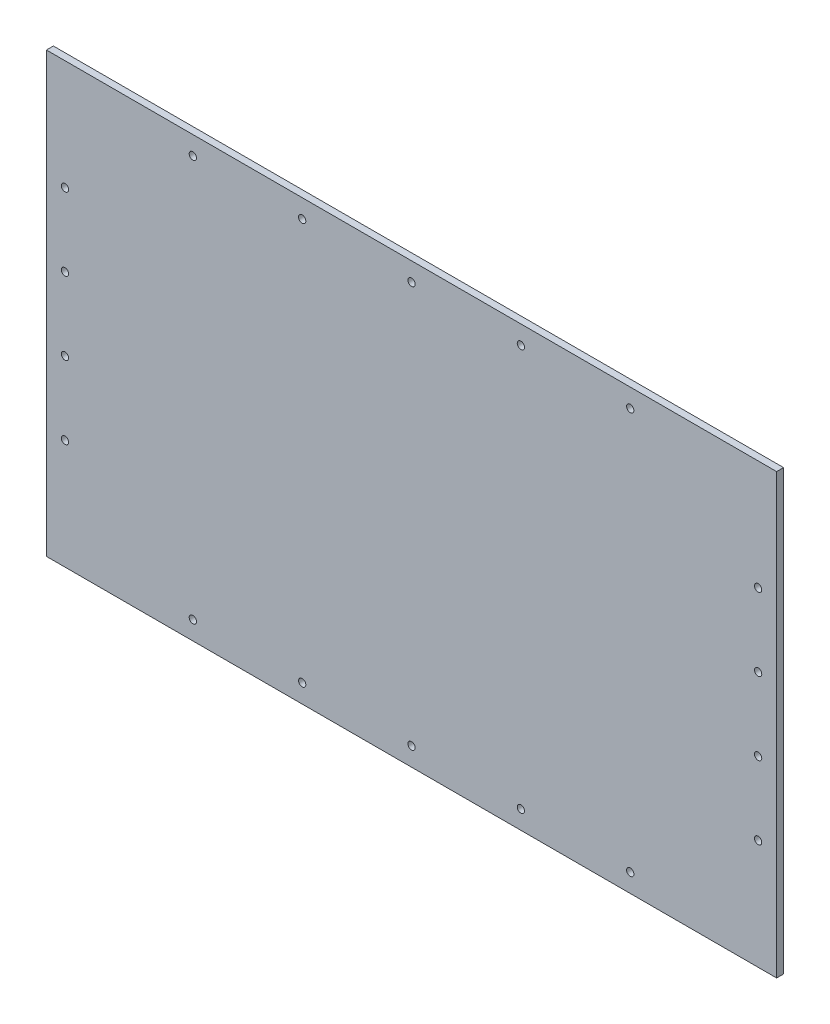
SolidWorks part; units mm, degrees
ref_plane "前基準面" through (0, 0, 0) normal (0, 0, 1) x (1, 0, 0)
ref_plane "上基準面" through (0, 0, 0) normal (0, 1, 0) x (1, 0, 0)
ref_plane "右基準面" through (0, 0, 0) normal (1, 0, 0) x (0, 0, -1)
sketch "草圖1" plane through (0, 0, 0) normal (0, 0, 1) x (1, 0, 0)
  line L1 (-250.4, 150.4) -> (250.4, 150.4)
  line L2 (-250.4, 150.4) -> (-250.4, -150.4)
  line L3 (-250.4, -150.4) -> (250.4, -150.4)
  line L4 (250.4, 150.4) -> (250.4, -150.4)
  line L5 (-250.4, 150.4) -> (250.4, -150.4) construction
  line L6 (-250.4, -150.4) -> (250.4, 150.4) construction
  point P0 (0, 0)
  dimension "D1" = 500.8
  dimension "D2" = 300.8
extrude "填料-伸長1" add sketch "草圖1" along normal blind 4.75 contours L1 L4 L3 L2
sketch "草圖3" plane through (0, 0, 0) normal (0, 0, -1) x (-1, 0, 0)
  line L0 (-250.4, 150.4) -> (-250.4, 137.7) construction
  line L1 (-250.4, 150.4) -> (-250.4, -150.4) construction
  line L2 (-250.4, 137.7) -> (-225, 137.7) construction
  line L3 (-225, 137.7) -> (-150, 137.7) construction
  circle A0 centre (-150, 137.7) radius 2.5
  circle A1 centre (-75, 137.7) radius 2.5
  circle A2 centre (0, 137.7) radius 2.5
  circle A3 centre (75, 137.7) radius 2.5
  circle A4 centre (150, 137.7) radius 2.5
  dimension "D4" = 5
  dimension "D1" = 12.7
  dimension "D2" = 25.4
  dimension "D3" = 75
  dimension "D5" = 5
extrude "除料-伸長1" cut sketch "草圖3" against normal blind 10
sketch "草圖4" plane through (0, 0, 0) normal (0, 0, -1) x (-1, 0, 0)
  line L0 (-250.4, 150.4) -> (-237.7, 150.4) construction
  line L1 (250.4, 150.4) -> (-250.4, 150.4) construction
  line L2 (-237.7, 150.4) -> (-237.7, 125) construction
  line L3 (-237.7, 125) -> (-237.7, 75) construction
  circle A0 centre (-237.7, 75) radius 2.5
  circle A1 centre (-237.7, 25) radius 2.5
  circle A2 centre (-237.7, -25) radius 2.5
  circle A3 centre (-237.7, -75) radius 2.5
  dimension "D4" = 5
  dimension "D1" = 12.7
  dimension "D2" = 25.4
  dimension "D3" = 50
  dimension "D5" = 4
extrude "除料-伸長2" cut sketch "草圖4" against normal blind 10
sketch "草圖5" plane through (0, 0, 0) normal (0, 0, -1) x (-1, 0, 0)
  line L0 (250.4, 150.4) -> (237.7, 150.4) construction
  line L1 (250.4, 150.4) -> (-250.4, 150.4) construction
  line L2 (237.7, 150.4) -> (237.7, 125) construction
  line L3 (237.7, 125) -> (237.7, 75) construction
  circle A0 centre (237.7, 75) radius 2.5
  circle A1 centre (237.7, 25) radius 2.5
  circle A2 centre (237.7, -25) radius 2.5
  circle A3 centre (237.7, -75) radius 2.5
  dimension "D4" = 5
  dimension "D1" = 12.7
  dimension "D2" = 25.4
  dimension "D3" = 50
  dimension "D5" = 4
extrude "除料-伸長3" cut sketch "草圖5" against normal blind 10
sketch "草圖6" plane through (0, 0, 0) normal (0, 0, -1) x (-1, 0, 0)
  line L0 (250.4, -150.4) -> (250.4, -137.7) construction
  line L1 (250.4, 150.4) -> (250.4, -150.4) construction
  line L2 (250.4, -137.7) -> (225, -137.7) construction
  line L3 (225, -137.7) -> (150, -137.7) construction
  circle A0 centre (150, -137.7) radius 2.5
  circle A1 centre (75, -137.7) radius 2.5
  circle A2 centre (0, -137.7) radius 2.5
  circle A3 centre (-75, -137.7) radius 2.5
  circle A4 centre (-150, -137.7) radius 2.5
  dimension "D4" = 5
  dimension "D1" = 12.7
  dimension "D2" = 25.4
  dimension "D3" = 75
  dimension "D5" = 5
extrude "除料-伸長4" cut sketch "草圖6" against normal blind 10
